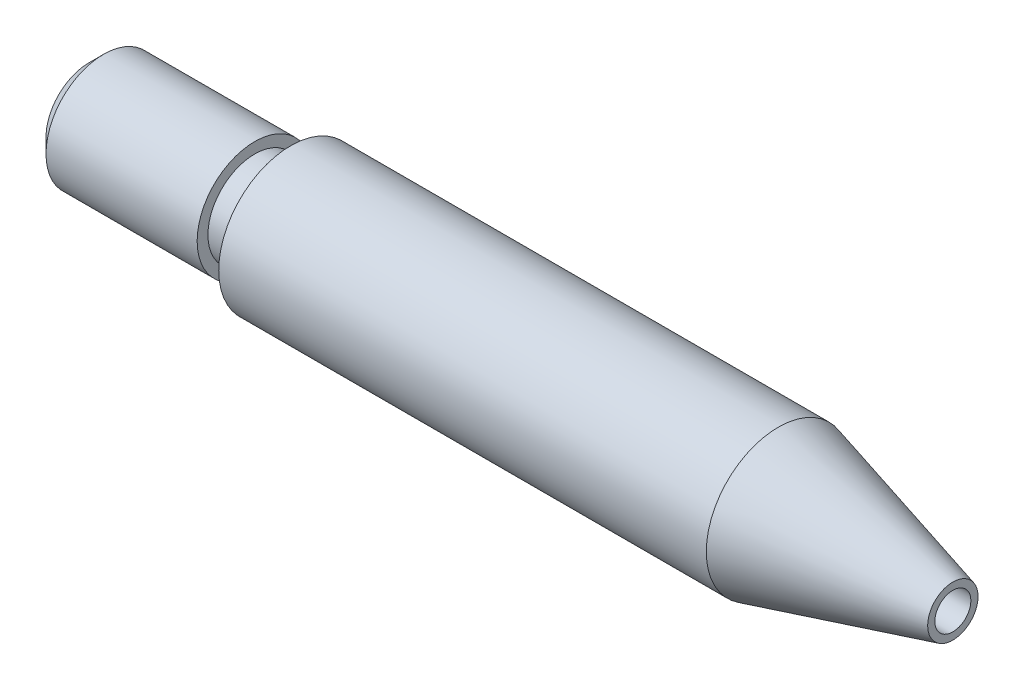
SolidWorks part; units mm, degrees
ref_plane "前视基准面" through (0, 0, 0) normal (0, 0, 1) x (1, 0, 0)
ref_plane "上视基准面" through (0, 0, 0) normal (0, 1, 0) x (1, 0, 0)
ref_plane "右视基准面" through (0, 0, 0) normal (1, 0, 0) x (0, 0, -1)
sketch "草图1" plane through (0, 0, 0) normal (0, 0, 1) x (1, 0, 0)
  line L0 (-15.3902, 0) -> (0.8351, 0) construction
  line L1 (-8.7283, 0) -> (-49.047, 0)
  line L2 (-49.047, 0) -> (-49.047, 4)
  line L3 (-49.047, 4) -> (-37.547, 4)
  line L4 (-37.547, 4) -> (-37.547, 3.25)
  line L5 (-37.547, 3.25) -> (-35.047, 3.25)
  line L6 (-35.047, 3.25) -> (-35.047, 5)
  line L7 (-35.047, 5) -> (-1.1761, 5)
  line L8 (-1.1761, 5) -> (10.953, 1.75)
  line L9 (10.953, 1.75) -> (10.953, 0)
  line L10 (10.953, 0) -> (-8.7283, 0)
  dimension "D1" = 1.75
  dimension "D2" = 5
  dimension "D3" = 15
  dimension "D4" = 11.5
  dimension "D5" = 2.5
  dimension "D6" = 60
  dimension "D7" = 1.75
  dimension "D8" = 4
revolve "旋转2" add sketch "草图1" angle 360 about L0
cosmetic thread "装饰螺纹线1" parameters "D2"=6.647
sketch "草图2" plane through (-49.047, 0, 0) normal (-1, 0, 0) x (0, 0, 1)
  circle A0 centre (0, 0) radius 1.75
  dimension "D1" = 3.5
extrude "切除-拉伸2" cut sketch "草图2" against normal blind 56
sketch "草图3" plane through (10.953, 0, 0) normal (1, 0, 0) x (0, 0, -1)
  circle A0 centre (0, 0) radius 1.25
  dimension "D1" = 2.5
extrude "切除-拉伸3" cut sketch "草图3" against normal through all
chamfer "倒角1" distance 1 angle 45 1 edges at (-49.047, 0, 4)
